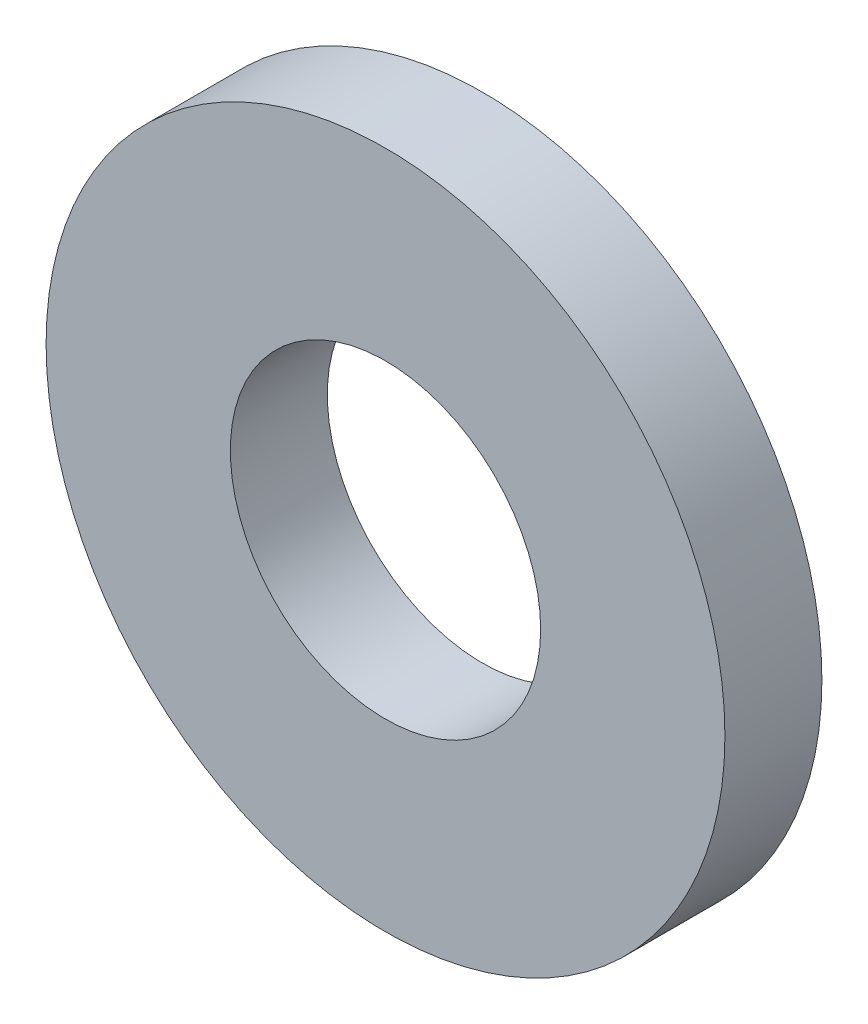
SolidWorks part; units mm, degrees
material "炭素鋼(普通)"
ref_plane "正面" through (0, 0, 0) normal (0, 0, 1) x (1, 0, 0)
ref_plane "平面" through (0, 0, 0) normal (0, 1, 0) x (1, 0, 0)
ref_plane "右側面" through (0, 0, 0) normal (1, 0, 0) x (0, 0, -1)
sketch "ｽｹｯﾁ1" plane through (0, 0, 0) normal (0, 0, 1) x (1, 0, 0)
  circle A0 centre (0, 0) radius 3.5
  circle A1 centre (0, 0) radius 1.6
  dimension "D1" = 7
  dimension "D2" = 3.2
extrude "ﾎﾞｽ - 押し出し1" add sketch "ｽｹｯﾁ1" along normal blind 1
